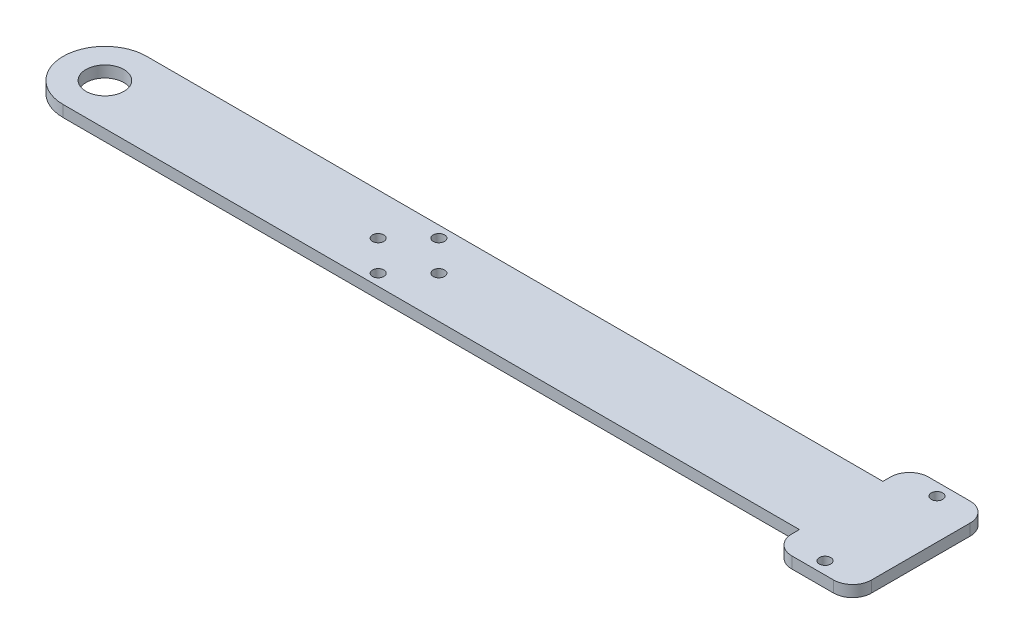
SolidWorks part; units mm, degrees
ref_plane "前视基准面" through (0, 0, 0) normal (0, 0, 1) x (1, 0, 0)
ref_plane "上视基准面" through (0, 0, 0) normal (0, 1, 0) x (1, 0, 0)
ref_plane "右视基准面" through (0, 0, 0) normal (1, 0, 0) x (0, 0, -1)
sketch "草图1" plane through (0, 0, 0) normal (0, 1, 0) x (1, 0, 0)
  line L0 (0, 0) -> (0, 22) construction
  line L1 (0, 11) -> (135, 11) construction
  line L2 (135, -2) -> (135, 24)
  line L3 (130, 29) -> (119, 29)
  line L4 (0, 22) -> (114, 22)
  line L5 (114, 22) -> (114, 24)
  line L6 (0, 0) -> (114, 0)
  line L7 (114, 0) -> (114, -2)
  line L8 (119, -7) -> (130, -7)
  line L9 (0, 11) -> (-80, 11) construction
  line L10 (-80, 0) -> (0, 0)
  line L11 (0, 22) -> (-80, 22)
  line L12 (124.5, 25.75) -> (124.5, -3.75) construction
  line L13 (0, 3) -> (0, 19) construction
  arc A0 (119, 29) -> (114, 24) centre (119, 24) ccw
  arc A1 (114, -2) -> (119, -7) centre (119, -2) ccw
  arc A2 (135, -2) -> (130, -7) centre (130, -2) cw
  arc A3 (135, 24) -> (130, 29) centre (130, 24) ccw
  circle A4 centre (-80, 11) radius 5
  arc A5 (-80, 22) -> (-80, 0) centre (-80, 11) ccw
  circle A6 centre (124.5, 25.75) radius 1.5
  circle A7 centre (124.5, -3.75) radius 1.5
  circle A8 centre (0, 19) radius 1.5
  circle A9 centre (8, 11) radius 1.5
  circle A10 centre (0, 3) radius 1.5
  circle A11 centre (-8, 11) radius 1.5
  point P8 (135, 11)
  point P14 (114, 29)
  point P21 (135, 29)
  point P29 (124.5, 11)
  point P34 (0, 11)
  dimension "D5" = 5
  dimension "D7" = 10
  dimension "D8" = 11
  dimension "D9" = 3
  dimension "D10" = 3
  dimension "D12" = 3
  dimension "D1" = 22
  dimension "D2" = 135
  dimension "D3" = 18
  dimension "D4" = 21
  dimension "D6" = 80
  dimension "D11" = 8
  dimension "D14" = 124.5
  dimension "D15" = 21
  dimension "D13" = 4
extrude "凸台-拉伸1" add sketch "草图1" along normal blind 3
